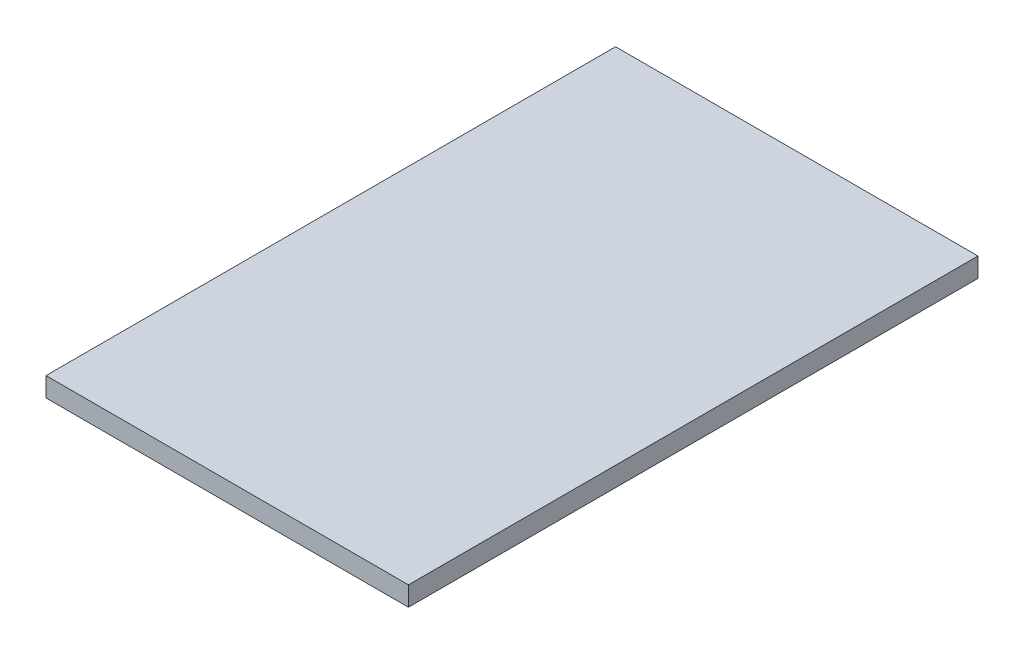
SolidWorks part; units mm, degrees
ref_plane "Plan de face" through (0, 0, 0) normal (0, 0, 1) x (1, 0, 0)
ref_plane "Plan de dessus" through (0, 0, 0) normal (0, 1, 0) x (1, 0, 0)
ref_plane "Plan de droite" through (0, 0, 0) normal (1, 0, 0) x (0, 0, -1)
sketch "Esquisse1" plane through (0, 0, 0) normal (0, 1, 0) x (1, 0, 0)
  line L1 (28, 44) -> (-28, 44)
  line L2 (28, 44) -> (28, -44)
  line L3 (28, -44) -> (-28, -44)
  line L4 (-28, 44) -> (-28, -44)
  line L5 (28, 44) -> (-28, -44) construction
  line L6 (28, -44) -> (-28, 44) construction
  point P0 (0, 0)
  dimension "D1" = 88
  dimension "D2" = 56
extrude "Boss.-Extru.1" add sketch "Esquisse1" along normal blind 3
